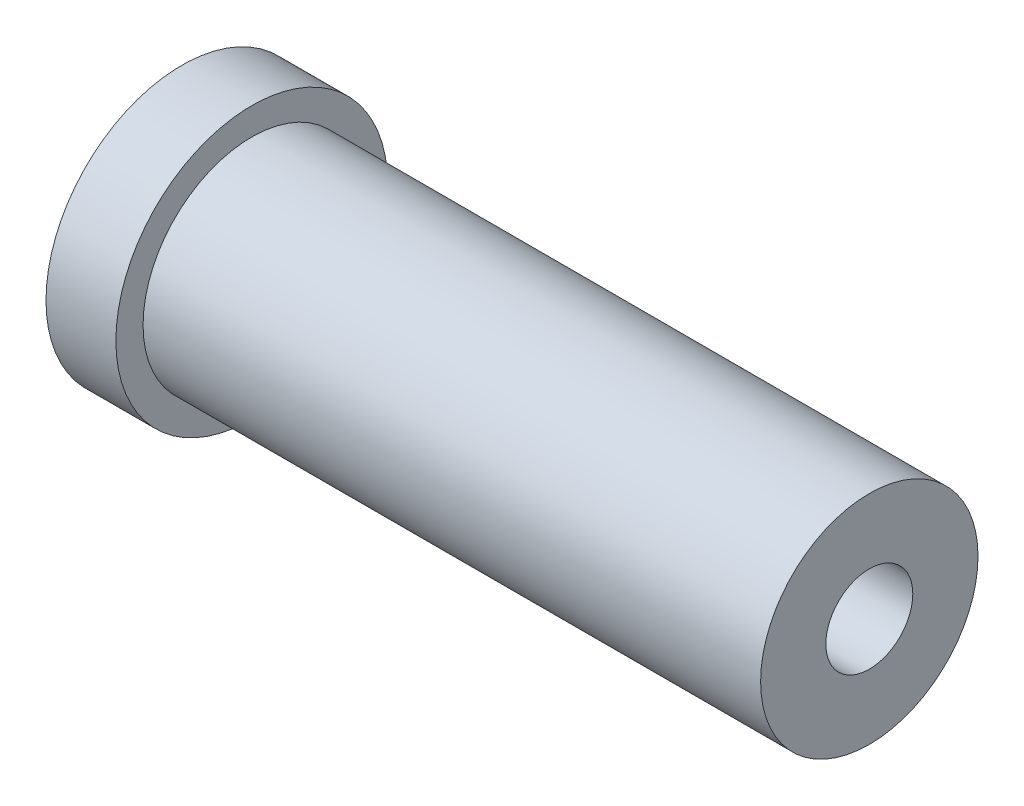
SolidWorks part; units mm, degrees
material "6061 Alloy"
ref_plane "Front Plane" through (0, 0, 0) normal (0, 0, 1) x (1, 0, 0)
ref_plane "Top Plane" through (0, 0, 0) normal (0, 1, 0) x (1, 0, 0)
ref_plane "Right Plane" through (0, 0, 0) normal (1, 0, 0) x (0, 0, -1)
sketch "Sketch1" plane through (0, 0, 0) normal (1, 0, 0) x (0, 0, -1)
  circle A0 centre (0, 0) radius 10
  dimension "D1" = 20
extrude "Boss-Extrude1" add sketch "Sketch1" along normal blind 63.25
sketch "Sketch2" plane through (0, 0, 0) normal (-1, 0, 0) x (0, 0, 1)
  circle A0 centre (0, 0) radius 12.5
  dimension "D1" = 25
extrude "Boss-Extrude2" add sketch "Sketch2" against normal blind 6.43
sketch "Sketch3" plane through (63.25, 0, 0) normal (1, 0, 0) x (0, 0, -1)
  circle A0 centre (0, 0) radius 4
  dimension "D1" = 8
extrude "Cut-Extrude1" cut sketch "Sketch3" against normal through all
